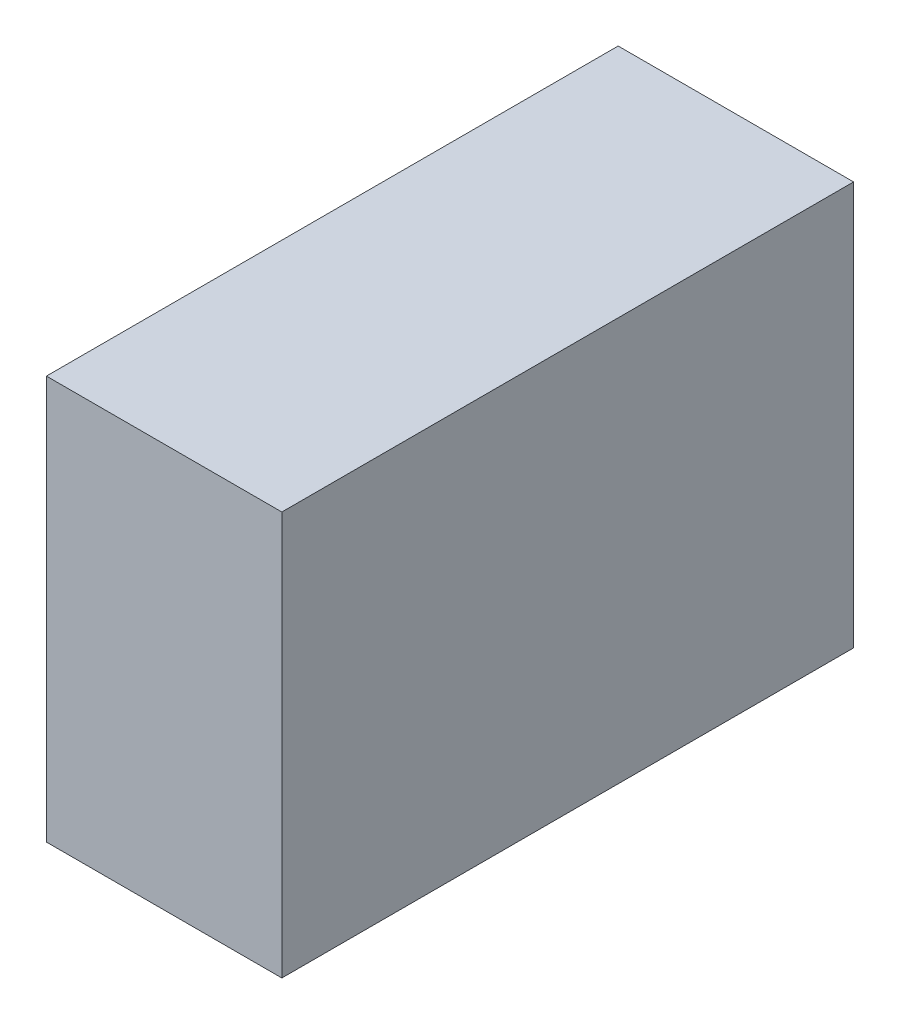
SolidWorks part; units mm, degrees
ref_plane "Front Plane" through (0, 0, 0) normal (0, 0, 1) x (1, 0, 0)
ref_plane "Top Plane" through (0, 0, 0) normal (0, 1, 0) x (1, 0, 0)
ref_plane "Right Plane" through (0, 0, 0) normal (1, 0, 0) x (0, 0, -1)
sketch "Sketch1" plane through (0, 0, 0) normal (0, 0, 1) x (1, 0, 0)
  line L1 (88.9, -152.4) -> (-88.9, -152.4)
  line L2 (88.9, -152.4) -> (88.9, 152.4)
  line L3 (88.9, 152.4) -> (-88.9, 152.4)
  line L4 (-88.9, -152.4) -> (-88.9, 152.4)
  line L5 (88.9, -152.4) -> (-88.9, 152.4) construction
  line L6 (88.9, 152.4) -> (-88.9, -152.4) construction
  point P0 (0, 0)
  dimension "D1" = 304.8
  dimension "D2" = 177.8
extrude "Boss-Extrude1" add sketch "Sketch1" along normal blind 431.8
